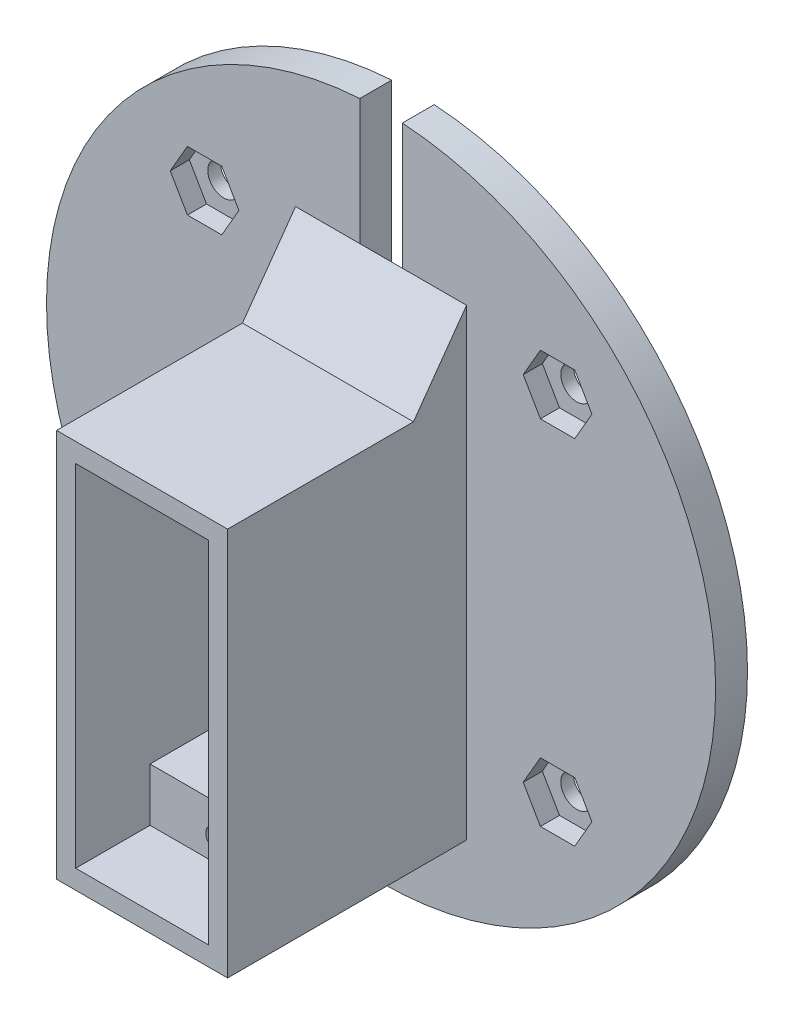
SolidWorks part; units mm, degrees
ref_plane "Alzado" through (0, 0, 0) normal (0, 0, 1) x (1, 0, 0)
ref_plane "Planta" through (0, 0, 0) normal (0, 1, 0) x (1, 0, 0)
ref_plane "Vista lateral" through (0, 0, 0) normal (1, 0, 0) x (0, 0, -1)
sketch "Croquis1" plane through (0, 0, 0) normal (0, 0, 1) x (1, 0, 0)
  circle A0 centre (-51.2357, 9.7866) radius 31.5
  dimension "D1" = 63
extrude "Saliente-Extruir1" add sketch "Croquis1" along normal blind 2.4
sketch "Croquis2" plane through (0, 0, 2.4) normal (0, 0, 1) x (1, 0, 0)
  line L0 (-51.2357, 9.7866) -> (-51.2357, -21.7134) construction
  line L1 (-51.2357, 9.7866) -> (-51.2357, 14.7866) construction
  line L2 (-51.2357, 14.7866) -> (-51.2357, 19.7866) construction
  line L3 (-51.2357, 19.7866) -> (-51.2357, 20.5866) construction
  line L4 (-51.2357, 20.5866) -> (-57.4857, 20.5866) construction
  line L6 (-57.4857, 20.5866) -> (-44.9857, 20.5866)
  line L7 (-57.4857, 20.5866) -> (-57.4857, -12.4134)
  line L8 (-57.4857, -12.4134) -> (-44.9857, -12.4134)
  line L9 (-44.9857, 20.5866) -> (-44.9857, -12.4134)
  line L14 (-59.2857, 22.3866) -> (-43.1857, 22.3866)
  line L15 (-59.2857, 22.3866) -> (-59.2857, -14.2134)
  line L16 (-59.2857, -14.2134) -> (-43.1857, -14.2134)
  line L17 (-43.1857, 22.3866) -> (-43.1857, -14.2134)
  circle A0 centre (-51.2357, 9.7866) radius 31.5 construction
  dimension "D4" = 6.25
  dimension "D5" = 12.5
  dimension "D6" = 33
  dimension "D7" = 1.8
  dimension "D8" = 1.8
  dimension "D9" = 1.8
  dimension "D10" = 1.8
  dimension "D11" = 7.5
extrude "Saliente-Extruir2" add sketch "Croquis2" along normal blind 22.5
sketch "Croquis5" plane through (0, 0, 2.4) normal (0, 0, 1) x (1, 0, 0)
  line L1 (-59.2857, 22.3866) -> (-43.1857, 22.3866)
  line L2 (-59.2857, 22.3866) -> (-59.2857, -14.2134)
  line L3 (-59.2857, -14.2134) -> (-43.1857, -14.2134)
  line L4 (-43.1857, 22.3866) -> (-43.1857, -14.2134)
extrude "Cortar-Extruir2" cut sketch "Croquis5" against normal blind 9
sketch "Croquis6" plane through (0, 0, 0) normal (0, 0, -1) x (-1, 0, 0)
  line L6 (51.2357, 9.7866) -> (73.5095, 32.0605) construction
  line L7 (73.5095, 32.0605) -> (73.5095, -12.4873) construction
  line L8 (73.5095, -12.4873) -> (28.9618, 32.0605) construction
  line L9 (28.9618, 32.0605) -> (28.9618, -12.4873) construction
  line L10 (28.9618, -12.4873) -> (51.2357, 9.7866) construction
  line L11 (51.2357, 22.3866) -> (53.2357, 22.3866)
  line L12 (43.1857, 22.3866) -> (59.2857, 22.3866) construction
  line L13 (53.2357, 22.3866) -> (53.2357, 42.3866)
  line L14 (53.2357, 42.3866) -> (49.2357, 42.3866)
  line L15 (49.2357, 42.3866) -> (49.2357, 22.3866)
  line L16 (49.2357, 22.3866) -> (51.2357, 22.3866)
  circle A0 centre (51.2357, 9.7866) radius 31.5 construction
  circle A1 centre (34.6187, 26.4036) radius 1.5
  circle A2 centre (67.8527, 26.4036) radius 1.5
  circle A3 centre (67.8527, -6.8304) radius 1.5
  circle A4 centre (34.6187, -6.8304) radius 1.5
  dimension "D3" = 8
  dimension "D1" = 20
  dimension "D2" = 4
extrude "Cortar-Extruir3" cut sketch "Croquis6" against normal blind 2.4
sketch "Croquis7" plane through (0, 20.5866, 0) normal (0, -1, 0) x (1, 0, 0)
  line L0 (-57.4857, 24.9) -> (-57.4857, 2.4) construction
  line L1 (-57.4857, 17.9) -> (-44.9857, 17.9)
  line L2 (-57.4857, 17.9) -> (-57.4857, 8.9)
  line L3 (-57.4857, 8.9) -> (-44.9857, 8.9)
  line L4 (-44.9857, 17.9) -> (-44.9857, 8.9)
  line L5 (-44.9857, 24.9) -> (-44.9857, 2.4) construction
  line L6 (-44.9857, 24.9) -> (-57.4857, 24.9) construction
  dimension "D1" = 9
  dimension "D2" = 7
extrude "Saliente-Extruir3" add sketch "Croquis7" along normal up to vertex (33 mm away)
sketch "Croquis8" plane through (0, 0, 17.9) normal (0, 0, 1) x (1, 0, 0)
  line L0 (-44.9857, -12.4134) -> (-44.9857, 20.5866) construction
  line L1 (-44.9857, -7.4134) -> (-57.4857, -7.4134)
  line L2 (-44.9857, -7.4134) -> (-44.9857, 15.5866)
  line L4 (-57.4857, -7.4134) -> (-57.4857, 15.5866)
  line L5 (-57.4857, -12.4134) -> (-57.4857, 20.5866) construction
  line L6 (-44.9857, -12.4134) -> (-57.4857, -12.4134) construction
  line L9 (-44.9857, 15.5866) -> (-49.2357, 15.5866)
  line L10 (-49.2357, 15.5866) -> (-49.2357, 17.5866)
  line L11 (-49.2357, 17.5866) -> (-53.2357, 17.5866)
  line L12 (-53.2357, 17.5866) -> (-53.2357, 15.5866)
  line L13 (-53.2357, 15.5866) -> (-57.4857, 15.5866)
  line L14 (-44.9857, 20.5866) -> (-57.4857, 20.5866) construction
  circle A0 centre (-51.2357, -10.4134) radius 1
  circle A1 centre (-51.2357, 18.6366) radius 1
  dimension "D3" = 2
  dimension "D6" = 1.95
  dimension "D1" = 5
  dimension "D2" = 5
  dimension "D4" = 4
  dimension "D5" = 2
  dimension "D7" = 2
extrude "Cortar-Extruir5" cut sketch "Croquis8" against normal blind 9
sketch "Croquis9" plane through (-44.9857, 0, 0) normal (-1, 0, 0) x (0, 0, 1)
  line L0 (8.9, -7.4134) -> (3.9, -12.4134)
  line L1 (8.9, -12.4134) -> (2.4, -12.4134) construction
  line L2 (3.9, -12.4134) -> (8.9, -12.4134)
  line L3 (8.9, -12.4134) -> (8.9, -7.4134)
  line L4 (8.9, 15.5866) -> (3.9, 20.5866)
  line L5 (8.9, 20.5866) -> (2.4, 20.5866) construction
  line L6 (3.9, 20.5866) -> (8.9, 20.5866)
  line L7 (8.9, 20.5866) -> (8.9, 15.5866)
extrude "Saliente-Extruir4" add sketch "Croquis9" along normal up to vertex (12.5 mm away)
sketch "Croquis10" plane through (0, 0, 8.9) normal (0, 0, 1) x (1, 0, 0)
  line L1 (-53.2357, 15.5866) -> (-49.2357, 15.5866)
  line L2 (-53.2357, 15.5866) -> (-53.2357, 17.5866)
  line L3 (-53.2357, 17.5866) -> (-49.2357, 17.5866)
  line L4 (-49.2357, 15.5866) -> (-49.2357, 17.5866)
extrude "Cortar-Extruir6" cut sketch "Croquis10" against normal blind 9
sketch "Croquis11" plane through (0, 0, 2.4) normal (0, 0, -1) x (-1, 0, 0)
  line L0 (49.2357, 22.3866) -> (43.1857, 22.3866)
  line L1 (43.1857, 22.3866) -> (43.1857, -14.2134)
  line L2 (43.1857, -14.2134) -> (59.2857, -14.2134)
  line L3 (59.2857, -14.2134) -> (59.2857, 22.3866)
  line L4 (59.2857, 22.3866) -> (53.2357, 22.3866)
  line L5 (53.2357, 22.3866) -> (53.2357, 20.5866)
  line L6 (44.9857, 20.5866) -> (57.4857, 20.5866) construction
  line L7 (53.2357, 20.5866) -> (57.4857, 20.5866)
  line L8 (57.4857, 20.5866) -> (57.4857, 10.5866)
  line L9 (57.4857, 20.5866) -> (57.4857, -12.4134) construction
  line L10 (57.4857, 10.5866) -> (44.9857, 10.5866)
  line L11 (44.9857, -12.4134) -> (44.9857, 20.5866) construction
  line L12 (44.9857, 10.5866) -> (44.9857, 20.5866)
  line L13 (44.9857, 20.5866) -> (49.2357, 20.5866)
  line L14 (49.2357, 20.5866) -> (49.2357, 22.3866)
extrude "Saliente-Extruir5" add sketch "Croquis11" along normal up to vertex (2.4 mm away)
sketch "Croquis12" plane through (-43.1857, 0, 0) normal (1, 0, 0) x (0, 0, -1)
  line L0 (-2.4, 22.3866) -> (-7.4, 22.3866)
  line L1 (-24.9, 22.3866) -> (-2.4, 22.3866) construction
  line L2 (-7.4, 22.3866) -> (-2.4, 29.3866)
  line L3 (-2.4, 29.3866) -> (-2.4, 22.3866)
extrude "Saliente-Extruir6" add sketch "Croquis12" against normal up to vertex (16.1 mm away)
sketch "Croquis13" plane through (0, 0, 2.4) normal (0, 0, 1) x (1, 0, 0)
  line L1 (-31.3855, -6.8304) -> (-33.0021, -4.0304)
  line L2 (-33.0021, -4.0304) -> (-36.2352, -4.0304)
  line L3 (-36.2352, -4.0304) -> (-37.8518, -6.8304)
  line L4 (-37.8518, -6.8304) -> (-36.2352, -9.6304)
  line L5 (-36.2352, -9.6304) -> (-33.0021, -9.6304)
  line L6 (-33.0021, -9.6304) -> (-31.3855, -6.8304)
  line L7 (-64.6195, -6.8304) -> (-66.2361, -4.0304)
  line L8 (-66.2361, -4.0304) -> (-69.4693, -4.0304)
  line L9 (-69.4693, -4.0304) -> (-71.0858, -6.8304)
  line L10 (-71.0858, -6.8304) -> (-69.4693, -9.6304)
  line L11 (-69.4693, -9.6304) -> (-66.2361, -9.6304)
  line L12 (-66.2361, -9.6304) -> (-64.6195, -6.8304)
  line L13 (-37.8518, 26.4036) -> (-36.2352, 23.6036)
  line L14 (-36.2352, 23.6036) -> (-33.0021, 23.6036)
  line L15 (-33.0021, 23.6036) -> (-31.3855, 26.4036)
  line L16 (-31.3855, 26.4036) -> (-33.0021, 29.2036)
  line L17 (-33.0021, 29.2036) -> (-36.2352, 29.2036)
  line L18 (-36.2352, 29.2036) -> (-37.8518, 26.4036)
  line L19 (-71.0858, 26.4036) -> (-69.4693, 23.6036)
  line L20 (-69.4693, 23.6036) -> (-66.2361, 23.6036)
  line L21 (-66.2361, 23.6036) -> (-64.6195, 26.4036)
  line L22 (-64.6195, 26.4036) -> (-66.2361, 29.2036)
  line L23 (-66.2361, 29.2036) -> (-69.4693, 29.2036)
  line L24 (-69.4693, 29.2036) -> (-71.0858, 26.4036)
  circle A0 centre (-34.6187, -6.8304) radius 2.8 construction
  circle A1 centre (-67.8527, -6.8304) radius 2.8 construction
  circle A2 centre (-34.6187, 26.4036) radius 2.8 construction
  circle A3 centre (-67.8527, 26.4036) radius 2.8 construction
  dimension "D1" = 5.6
  dimension "D2" = 5.6
extrude "Cortar-Extruir7" cut sketch "Croquis13" against normal blind 1.8
sketch "Croquis14" plane through (0, 0, 0) normal (0, 0, -1) x (-1, 0, 0)
  line L0 (53.2357, 41.223) -> (53.2357, 20.5866)
  line L1 (53.2357, 20.5866) -> (57.4857, 20.5866)
  line L2 (57.4857, 20.5866) -> (57.4857, 10.5866)
  line L3 (57.4857, 10.5866) -> (44.9857, 10.5866)
  line L4 (44.9857, 10.5866) -> (44.9857, 20.5866)
  line L5 (44.9857, 20.5866) -> (49.2357, 20.5866)
  line L6 (49.2357, 20.5866) -> (49.2357, 41.223)
  arc A0 (53.2357, 41.223) -> (49.2357, 41.223) centre (51.2357, 9.7866) cw
  circle A1 centre (67.8527, -6.8304) radius 1.5
  circle A2 centre (34.6187, -6.8304) radius 1.5
  circle A3 centre (34.6187, 26.4036) radius 1.5
  circle A4 centre (67.8527, 26.4036) radius 1.5
extrude "Saliente-Extruir7" add sketch "Croquis14" along normal blind 0.6
sketch "Croquis15" plane through (0, -7.4134, 0) normal (0, 1, 0) x (1, 0, 0)
  line L0 (-44.9857, -16.4) -> (-57.4857, -16.4) construction
  line L1 (-44.9857, -8.9) -> (-44.9857, -17.9) construction
  line L2 (-57.4857, -8.9) -> (-57.4857, -17.9) construction
  line L3 (-57.4857, -17.9) -> (-44.9857, -17.9) construction
  dimension "D1" = 1.5
ref_plane "Plano1" through (0, 0, 16.4) normal (0, 0, 1) x (1, 0, 0)
